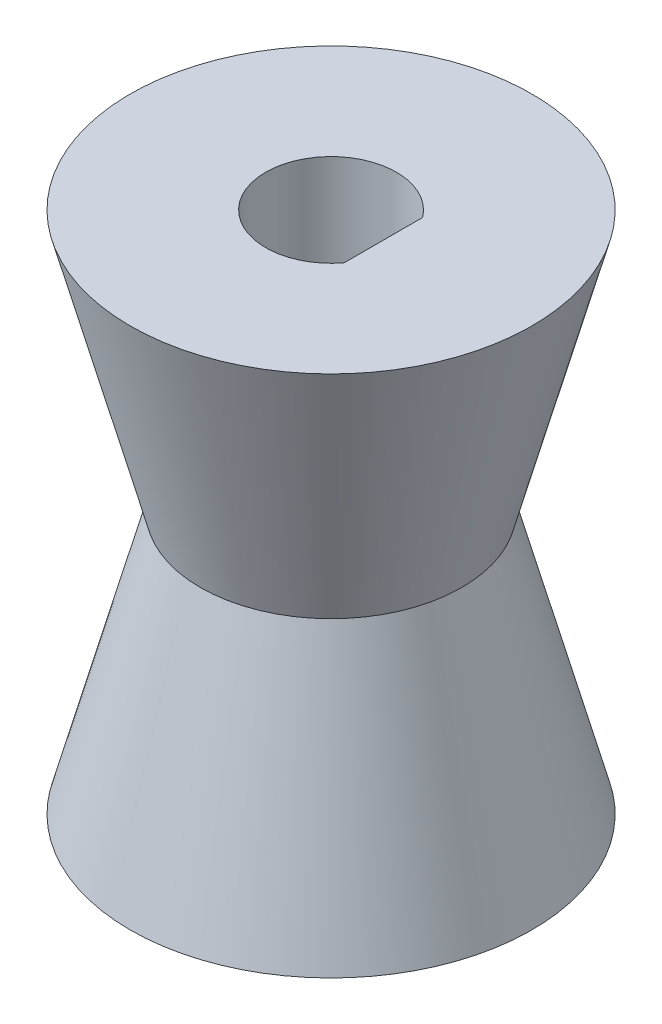
SolidWorks part; units mm, degrees
ref_plane "Спереди" through (0, 0, 0) normal (0, 0, 1) x (1, 0, 0)
ref_plane "Сверху" through (0, 0, 0) normal (0, 1, 0) x (1, 0, 0)
ref_plane "Справа" through (0, 0, 0) normal (1, 0, 0) x (0, 0, -1)
sketch "Эскиз1" plane through (0, 0, 0) normal (0, 1, 0) x (1, 0, 0)
  line L0 (2, 1.5) -> (2, -1.5)
  circle A0 centre (0, 0) radius 2.5 construction
  arc A1 (2, 1.5) -> (2, -1.5) centre (0, 0) ccw
  circle A2 centre (0, 0) radius 5
  point P5 (-2.5, 0)
  dimension "D1" = 5
  dimension "D3" = 10
  dimension "D2" = 4.5
extrude "Вытянуть1" add sketch "Эскиз1" along normal blind 10
draft "Уклон1" type of draft neutral plane draft angle 15 faces to draft 1 face at (0, 10, 5) neutral plane through (0, 10, 0) neutral plane normal (0, 1, 0) parameters "D1"=15
sketch "Эскиз3" plane through (0, 10, 0) normal (0, 1, 0) x (1, 0, 0)
  line L0 (2, 1.5) -> (2, -1.5)
  arc A0 (2, 1.5) -> (2, -1.5) centre (0, 0) ccw
  arc A1 (2, 1.5) -> (2, -1.5) centre (0, 0) ccw construction
  circle A2 centre (0, 0) radius 7.6795
  circle A4 centre (0, 0) radius 7.6795 construction
extrude "Вытянуть2" add sketch "Эскиз3" along normal blind 10
draft "Уклон2" type of draft neutral plane draft angle 15 faces to draft 1 face at (0, 20, 7.6795) neutral plane through (0, 20, 0) neutral plane normal (0, 1, 0) reverse direction yes parameters "D1"=15
